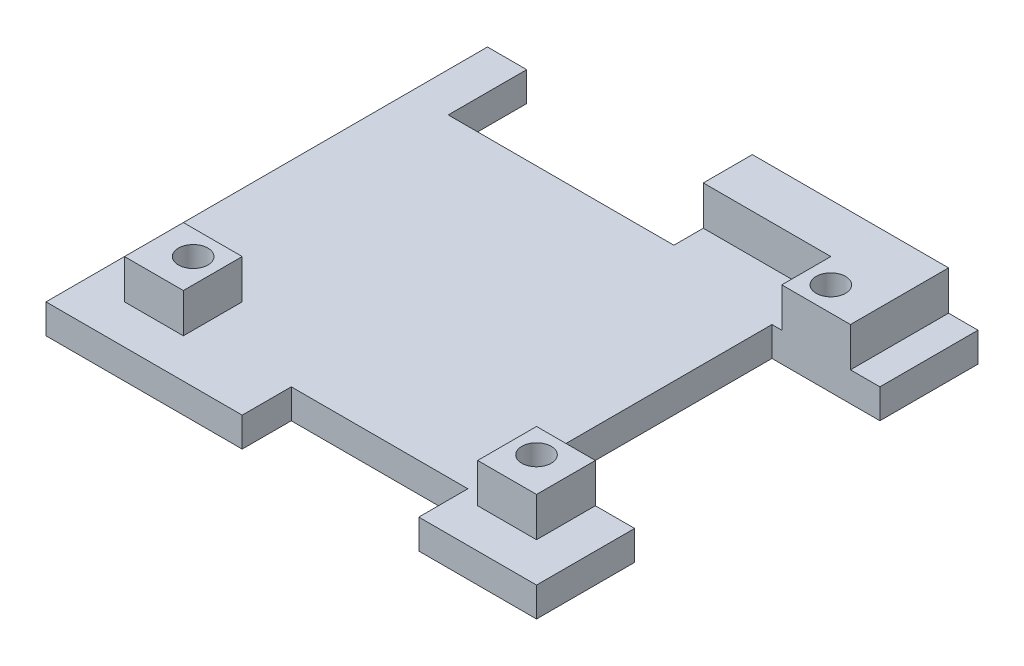
SolidWorks part; units mm, degrees
ref_plane "前视基准面" through (0, 0, 0) normal (0, 0, 1) x (1, 0, 0)
ref_plane "上视基准面" through (0, 0, 0) normal (0, 1, 0) x (1, 0, 0)
ref_plane "右视基准面" through (0, 0, 0) normal (1, 0, 0) x (0, 0, -1)
sketch "草图1" plane through (0, 0, 0) normal (0, 1, 0) x (1, 0, 0)
  line L1 (-25, 22.5) -> (25, 22.5)
  line L2 (-25, 22.5) -> (-25, -22.5)
  line L3 (-25, -22.5) -> (25, -22.5)
  line L4 (25, 22.5) -> (25, -22.5)
  line L5 (0, -22.5) -> (0, 22.5) construction
  line L6 (-25, 0) -> (25, 0) construction
  point P0 (0, 0)
  dimension "D1" = 45
  dimension "D2" = 50
extrude "凸台-拉伸1" add sketch "草图1" along normal blind 3
sketch "草图2" plane through (0, 3, 0) normal (0, 1, 0) x (1, 0, 0)
  line L0 (25, 22.5) -> (-25, 22.5) construction
  line L1 (22, 22.5) -> (15, 22.5)
  line L2 (22, 22.5) -> (22, 12.5)
  line L3 (22, 12.5) -> (15, 12.5)
  line L4 (15, 17.5) -> (15, 12.5)
  line L5 (25, -22.5) -> (25, 22.5) construction
  line L6 (2, 22.5) -> (15, 22.5)
  line L7 (2, 22.5) -> (2, 17.5)
  line L8 (2, 17.5) -> (15, 17.5)
  line L9 (-25, -22.5) -> (25, -22.5) construction
  line L10 (-21, -12.5) -> (-15, -12.5)
  line L11 (-21, -12.5) -> (-21, -18.5)
  line L12 (-21, -18.5) -> (-15, -18.5)
  line L13 (-15, -12.5) -> (-15, -18.5)
  line L14 (-25, 22.5) -> (-25, -22.5) construction
  line L16 (15, -12.5) -> (21, -12.5)
  line L17 (15, -12.5) -> (15, -18.5)
  line L18 (15, -18.5) -> (21, -18.5)
  line L19 (21, -12.5) -> (21, -18.5)
  dimension "D1" = 3
  dimension "D2" = 10
  dimension "D3" = 20
  dimension "D4" = 5
  dimension "D5" = 7
  dimension "D6" = 6
  dimension "D7" = 4
  dimension "D8" = 4
  dimension "D9" = 6
  dimension "D10" = 4
  dimension "D11" = 4
extrude "凸台-拉伸2" add sketch "草图2" along normal blind 4
sketch "草图4" plane through (0, 3, 0) normal (0, 1, 0) x (1, 0, 0)
  line L0 (2, 22.5) -> (-25, 22.5) construction
  line L1 (-21, 22.5) -> (2, 22.5)
  line L2 (-21, 22.5) -> (-21, 14.5)
  line L3 (-21, 14.5) -> (2, 14.5)
  line L4 (2, 22.5) -> (2, 14.5)
  line L5 (2, 22.5) -> (2, 17.5) construction
  line L6 (-25, 22.5) -> (-25, -22.5) construction
  line L8 (25, 12.5) -> (14, 12.5)
  line L9 (25, -22.5) -> (25, 22.5) construction
  line L10 (14, 12.5) -> (14, -12.5)
  line L11 (14, -12.5) -> (25, -12.5)
  line L14 (-5, -22.5) -> (-5, -17.5)
  line L15 (-25, -22.5) -> (25, -22.5) construction
  line L16 (-5, -17.5) -> (13, -17.5)
  line L17 (13, -17.5) -> (13, -22.5)
  line L18 (13, -22.5) -> (-5, -22.5)
  line L19 (25, -12.5) -> (25, 12.5)
  line L20 (15, 12.5) -> (22, 12.5) construction
  point P24 (13, -20)
  dimension "D1" = 4
  dimension "D2" = 8
  dimension "D3" = 5
  dimension "D4" = 18
  dimension "D5" = 11
  dimension "D6" = 25
  dimension "D7" = 12
extrude "切除-拉伸1" cut sketch "草图4" against normal blind 4
sketch "草图5" plane through (0, 7, 0) normal (0, 1, 0) x (1, 0, 0)
  line L0 (0, 0) -> (0, -38.5208) construction
  line L1 (0, 0) -> (28.3141, 0) construction
  point P0 (-17.5, -15)
  point P1 (17.5, -15)
  point P2 (17.5, 15)
  dimension "D1" = 30
  dimension "D2" = 35
hole_wizard "孔1" positions "3D草图2" profile "草图7" legacy end condition through all
sketch3d "3D草图2"
  point P2 (-17.5, 7, 15)
  point P5 (17.5, 7, 15)
  point P8 (17.5, 7, -15)
sketch "草图7" plane through (-17.5, 7, 15) normal (1, 0, 0) x (0, 0, 1)
  line L0 (0, 0) -> (0, 7)
  line L1 (0, 7) -> (1.5, 7)
  line L2 (1.5, 7) -> (1.5, 0)
  line L3 (1.5, 0) -> (0, 0)
  line L4 (0, 110) -> (0, -10) construction
  dimension "直径" = 3
  dimension "深度" = 7
